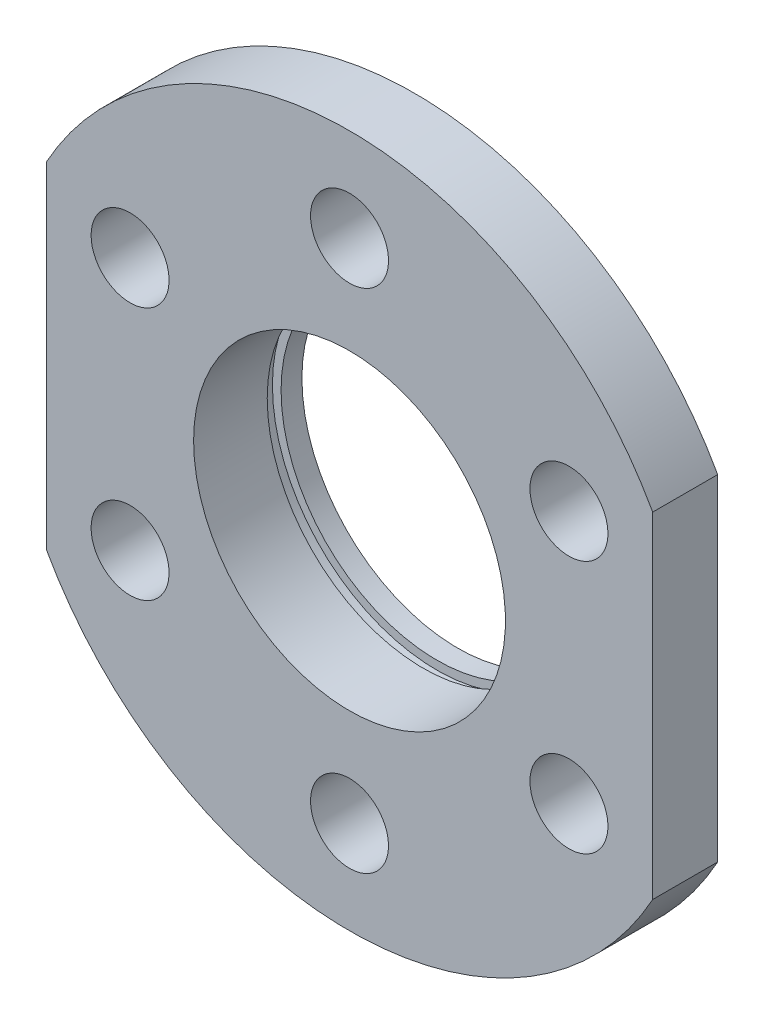
SolidWorks part; units mm, degrees
material "Low Carbon Steel"
ref_plane "Front Plane" through (0, 0, 0) normal (0, 0, 1) x (1, 0, 0)
ref_plane "Top Plane" through (0, 0, 0) normal (0, 1, 0) x (1, 0, 0)
ref_plane "Right Plane" through (0, 0, 0) normal (1, 0, 0) x (0, 0, -1)
sketch "Sketch1" plane through (0, 0, 0) normal (1, 0, 0) x (0, 0, -1)
  line L0 (13.6275, 0) -> (-52.9423, 0) construction
  line L1 (0, 18) -> (8.5, 18)
  line L2 (12.5038, 18) -> (12.5038, 23.5)
  line L3 (12.5038, 23.5) -> (7.5, 23.5)
  line L4 (7.5, 23.5) -> (7.5, 40)
  line L5 (7.5, 40) -> (0, 40)
  line L6 (0, 40) -> (0, 18)
  line L7 (8.5, 18) -> (8.5, 19)
  line L8 (8.5, 19) -> (10.1, 19)
  line L9 (10.1, 19) -> (10.1, 18)
  line L10 (10.1, 18) -> (12.5038, 18)
  dimension "D1" = 80
  dimension "D2" = 47
  dimension "D3" = 36
  dimension "D4" = 7.5
  dimension "D5" = 5.0038
  dimension "D6" = 38
  dimension "D7" = 1.6
  dimension "D8" = 8.5
revolve "Revolve1" add sketch "Sketch1" angle 360 about L0
hole_wizard "Ø9.0 (9) Diameter Hole1" positions "Sketch3" profile "Sketch2" hole size "Ø9.0" standard "Ansi Metric" end condition through all
sketch "Sketch3" plane through (0, 0, -7.5) normal (0, 0, -1) x (-1, 0, 0)
  point P0 (0, 29.25)
  dimension "D1" = 29.25
sketch "Sketch2" plane through (0, 29.25, -7.5) normal (1, 0, 0) x (0, 1, 0)
  line L0 (0, 0) -> (0, 7.5)
  line L1 (0, 7.5) -> (4.5, 7.5)
  line L2 (4.5, 7.5) -> (4.5, 0)
  line L5 (4.5, 0) -> (0, 0)
  line L11 (0, -6.35) -> (0, 107.95) construction
  dimension "Thru Hole Dia." = 9
  dimension "Thru Hole Depth" = 7.5
pattern_circular "CirPattern1" count 6 over 360 about axis through (0, 0, 0) along (0, 0, 1) of "Ø9.0 (9) Diameter Hole1"
chamfer "Chamfer1" distance 1 angle 45 1 edges at (-23.5, 0, -12.5038)
sketch "Sketch4" plane through (0, 0, 0) normal (0, 0, 1) x (1, 0, 0)
  line L0 (-35, 19.3649) -> (-35, -19.3649)
  line L1 (35, 19.3649) -> (35, -19.3649)
  circle A0 centre (0, 0) radius 40 construction
  arc A1 (-35, 19.3649) -> (-35, -19.3649) centre (0, 0) ccw
  arc A2 (35, -19.3649) -> (35, 19.3649) centre (0, 0) ccw
  dimension "D1" = 35
extrude "Extrude1" cut sketch "Sketch4" against normal through all
other "Freeze***"
